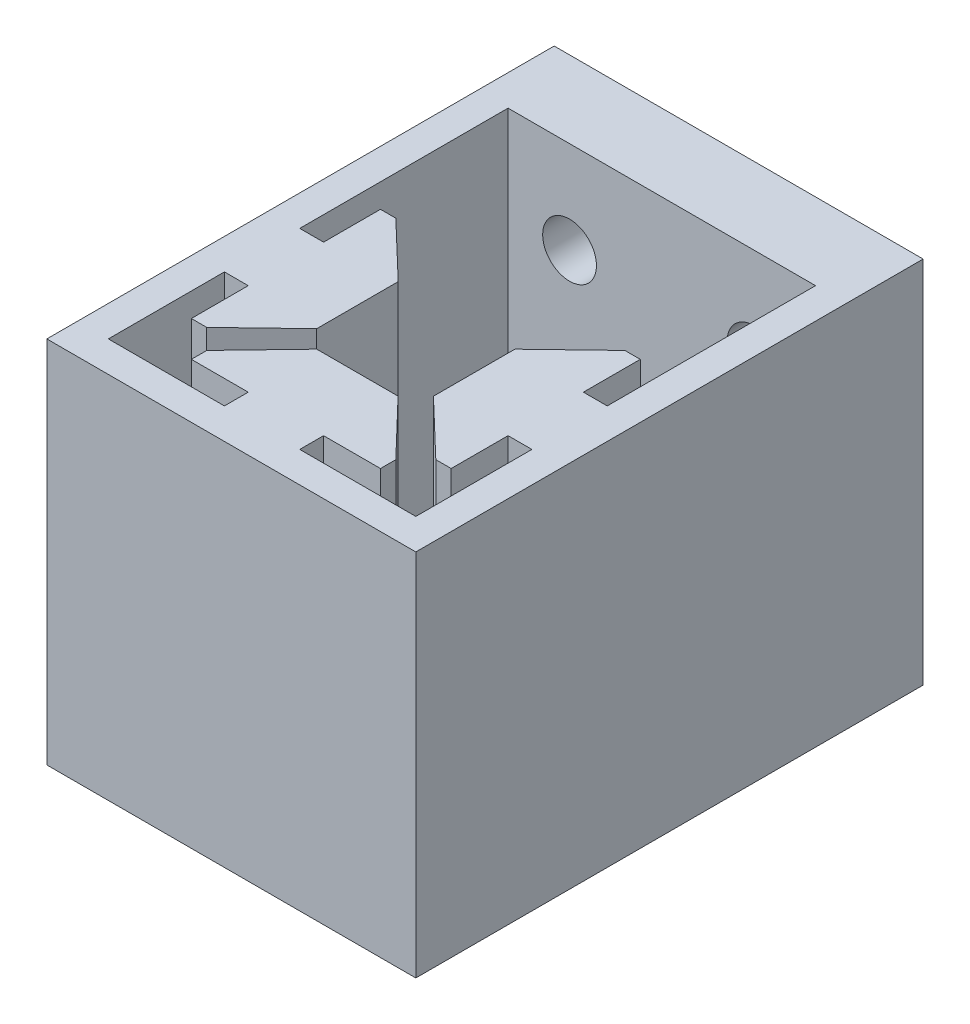
SolidWorks part; units mm, degrees
ref_plane "Plan de face" through (0, 0, 0) normal (0, 0, 1) x (1, 0, 0)
ref_plane "Plan de dessus" through (0, 0, 0) normal (0, 1, 0) x (1, 0, 0)
ref_plane "Plan de droite" through (0, 0, 0) normal (1, 0, 0) x (0, 0, -1)
sketch "Esquisse1" plane through (0, 0, 0) normal (0, 1, 0) x (1, 0, 0)
  line L1 (-12, 14) -> (12, 14)
  line L2 (-12, 14) -> (-12, -14)
  line L3 (-12, -14) -> (12, -14)
  line L4 (12, 14) -> (12, -14)
  line L5 (-12, 14) -> (12, -14) construction
  line L6 (-12, -14) -> (12, 14) construction
  point P0 (0, 0)
extrude "Boss.-Extru.1" add sketch "Esquisse1" along normal blind 24
sketch "Esquisse3" plane through (0, 24, 0) normal (0, 1, 0) x (1, 0, 0)
  line L0 (-10, -12) -> (-2.45, -12)
  line L1 (-2.45, -12) -> (-2.45, -10.45)
  line L2 (-2.45, -10.45) -> (-6.15, -10.45)
  line L3 (-6.15, -10.45) -> (-6.15, -9.45)
  line L4 (-6.15, -9.45) -> (-2.6456, -5.8)
  line L5 (-2.6456, -5.8) -> (2.6456, -5.8)
  line L6 (2.6456, -5.8) -> (6.15, -9.45)
  line L7 (6.15, -9.45) -> (6.15, -10.45)
  line L8 (6.15, -10.45) -> (2.45, -10.45)
  line L9 (2.45, -10.45) -> (2.45, -12)
  line L10 (2.45, -12) -> (10, -12)
  line L11 (10, -12) -> (10, -4.45)
  line L12 (10, -4.45) -> (8.45, -4.45)
  line L13 (8.45, -4.45) -> (8.45, -8.15)
  line L14 (8.45, -8.15) -> (7.45, -8.15)
  line L16 (3.8, -4.6544) -> (3.8, 0.6456)
  line L19 (8.45, 0.45) -> (10, 0.45)
  line L20 (10, 0.45) -> (10, 8)
  line L21 (10, 8) -> (2.45, 8)
  line L22 (2.45, 8) -> (2.45, 6.45)
  line L23 (2.45, 6.45) -> (6.15, 6.45)
  line L24 (6.15, 6.45) -> (6.15, 5.45)
  line L28 (-6.15, 5.45) -> (-6.15, 6.45)
  line L29 (-6.15, 6.45) -> (-2.45, 6.45)
  line L30 (-2.45, 6.45) -> (-2.45, 8)
  line L31 (-2.45, 8) -> (-10, 8)
  line L32 (-10, 8) -> (-10, 0.45)
  line L33 (-10, 0.45) -> (-8.45, 0.45)
  line L34 (-8.45, 0.45) -> (-8.45, 4.15)
  line L35 (-8.45, 4.15) -> (-7.45, 4.15)
  line L36 (-7.45, 4.15) -> (-3.8, 0.6544)
  line L37 (-3.8, 0.6544) -> (-3.8, -4.6456)
  line L38 (-3.8, -4.6456) -> (-7.45, -8.15)
  line L39 (-7.45, -8.15) -> (-8.45, -8.15)
  line L40 (-8.45, -8.15) -> (-8.45, -4.45)
  line L41 (-8.45, -4.45) -> (-10, -4.45)
  line L42 (-10, -4.45) -> (-10, -12)
  line L43 (-12, 14) -> (-12, -14) construction
  line L44 (-12, -14) -> (12, -14) construction
  line L45 (12, -14) -> (12, 14) construction
  line L46 (12, 14) -> (-12, 14) construction
  line L47 (3.8, 0.6456) -> (7.45, 4.15)
  line L48 (7.45, 4.15) -> (8.45, 4.15)
  line L49 (8.45, 0.45) -> (8.45, 4.15)
  line L50 (7.45, -8.15) -> (3.8, -4.6544)
  line L52 (2.6456, 1.8) -> (-2.6456, 1.8)
  line L53 (-2.6456, 1.8) -> (-6.15, 5.45)
  line L54 (6.15, 5.45) -> (2.6456, 1.8)
  dimension "D1" = 2
  dimension "D2" = 2
  dimension "D3" = 2
  dimension "D4" = 2
  dimension "D5" = 6
  dimension "D6" = 6
  dimension "D7" = 7.55
  dimension "D8" = 1.55
  dimension "D9" = 3.7
  dimension "D10" = 1
  dimension "D11" = 2
  dimension "D12" = 5.06
  dimension "D13" = 6.2
  dimension "D14" = 1.55
  dimension "D15" = 3.7
  dimension "D16" = 1
  dimension "D17" = 5.06
  dimension "D18" = 7.55
  dimension "D19" = 7.55
  dimension "D20" = 1.55
  dimension "D21" = 3.7
  dimension "D22" = 2
  dimension "D23" = 6.2
  dimension "D24" = 1
  dimension "D25" = 3.7
  dimension "D26" = 1.55
  dimension "D27" = 5.06
  dimension "D28" = 7.55
  dimension "D29" = 7.55
  dimension "D30" = 7.55
  dimension "D31" = 1.55
  dimension "1.55" = 1.55
  dimension "D32" = 6.2
  dimension "D33" = 3.7
  dimension "D34" = 1
  dimension "D35" = 5.06
  dimension "D36" = 5.3
  dimension "D37" = 3.7
  dimension "D38" = 1
  dimension "D39" = 7.55
  dimension "D40" = 7.55
  dimension "D41" = 6.2
  dimension "D42" = 1.55
  dimension "D43" = 3.7
  dimension "D44" = 1.55
  dimension "D45" = 3.7
  dimension "D46" = 1
  dimension "D47" = 5.2911
  dimension "D48" = 1
  dimension "D49" = 5.06
extrude "Enlèv. mat.-Extru.1" cut sketch "Esquisse3" against normal blind 24
sketch "Esquisse5" plane through (0, 0, -14) normal (0, 0, -1) x (-1, 0, 0)
  line L0 (-12, 0) -> (-12, 24)
  line L1 (-12, 24) -> (12, 24)
  line L2 (12, 24) -> (12, 0)
  line L3 (12, 0) -> (-12, 0)
extrude "Boss.-Extru.2" add sketch "Esquisse5" along normal blind 5
sketch "Esquisse6" plane through (0, 24, 0) normal (0, 1, 0) x (1, 0, 0)
  line L0 (-10, 8) -> (-10, 14)
  line L1 (10, 8) -> (10, 14)
  line L2 (10, 14) -> (-10, 14)
  line L3 (-12, 19) -> (12, 19) construction
  line L48 (-10, -4.45) -> (-10, -12)
  line L49 (-8.45, -4.45) -> (-10, -4.45)
  line L50 (-8.45, -8.15) -> (-8.45, -4.45)
  line L51 (-7.45, -8.15) -> (-8.45, -8.15)
  line L52 (-3.8, -4.6456) -> (-7.45, -8.15)
  line L53 (-3.8, 0.6544) -> (-3.8, -4.6456)
  line L54 (-7.45, 4.15) -> (-3.8, 0.6544)
  line L55 (-8.45, 4.15) -> (-7.45, 4.15)
  line L56 (-8.45, 0.45) -> (-8.45, 4.15)
  line L57 (-10, 0.45) -> (-8.45, 0.45)
  line L58 (-10, 8) -> (-10, 0.45)
  line L59 (-2.45, 8) -> (-10, 8)
  line L60 (-2.45, 6.45) -> (-2.45, 8)
  line L61 (-6.15, 6.45) -> (-2.45, 6.45)
  line L62 (-6.15, 5.45) -> (-6.15, 6.45)
  line L63 (-2.6456, 1.8) -> (-6.15, 5.45)
  line L64 (2.6456, 1.8) -> (-2.6456, 1.8)
  line L65 (6.15, 5.45) -> (2.6456, 1.8)
  line L66 (6.15, 6.45) -> (6.15, 5.45)
  line L67 (2.45, 6.45) -> (6.15, 6.45)
  line L68 (2.45, 8) -> (2.45, 6.45)
  line L69 (10, 8) -> (2.45, 8)
  line L70 (10, 0.45) -> (10, 8)
  line L71 (8.45, 0.45) -> (10, 0.45)
  line L72 (8.45, 4.15) -> (8.45, 0.45)
  line L73 (7.45, 4.15) -> (8.45, 4.15)
  line L74 (3.8, 0.6456) -> (7.45, 4.15)
  line L75 (3.8, -4.6544) -> (3.8, 0.6456)
  line L76 (7.45, -8.15) -> (3.8, -4.6544)
  line L77 (8.45, -8.15) -> (7.45, -8.15)
  line L78 (8.45, -4.45) -> (8.45, -8.15)
  line L79 (10, -4.45) -> (8.45, -4.45)
  line L80 (10, -12) -> (10, -4.45)
  line L81 (2.45, -12) -> (10, -12)
  line L82 (2.45, -10.45) -> (2.45, -12)
  line L83 (6.15, -10.45) -> (2.45, -10.45)
  line L84 (6.15, -9.45) -> (6.15, -10.45)
  line L85 (2.6456, -5.8) -> (6.15, -9.45)
  line L86 (-2.6456, -5.8) -> (2.6456, -5.8)
  line L87 (-6.15, -9.45) -> (-2.6456, -5.8)
  line L88 (-6.15, -10.45) -> (-6.15, -9.45)
  line L89 (-2.45, -10.45) -> (-6.15, -10.45)
  line L90 (-2.45, -12) -> (-2.45, -10.45)
  line L91 (-10, -12) -> (-2.45, -12)
  line L103 (-2.45, 8) -> (-10, 8)
  line L104 (-2.45, 6.45) -> (-2.45, 8)
  line L105 (-6.15, 6.45) -> (-2.45, 6.45)
  line L106 (-6.15, 5.45) -> (-6.15, 6.45)
  line L107 (-2.6456, 1.8) -> (-6.15, 5.45)
  line L108 (2.6456, 1.8) -> (-2.6456, 1.8)
  line L109 (6.15, 5.45) -> (2.6456, 1.8)
  line L110 (6.15, 6.45) -> (6.15, 5.45)
  line L111 (2.45, 6.45) -> (6.15, 6.45)
  line L112 (2.45, 8) -> (2.45, 6.45)
  line L113 (10, 8) -> (2.45, 8)
  dimension "D1" = 5
  dimension "D2" = 0
extrude "Enlèv. mat.-Extru.6" cut sketch "Esquisse6" against normal blind 24
sketch "Esquisse7" plane through (0, 0, -19) normal (0, 0, -1) x (-1, 0, 0)
  line L0 (12, 24) -> (-12, 24) construction
  line L1 (-12, 24) -> (-12, 0) construction
  line L2 (12, 0) -> (12, 24) construction
  line L3 (-12, 0) -> (12, 0) construction
  circle A0 centre (-6, 18) radius 1.75
  circle A1 centre (-6, 6) radius 1.75
  circle A2 centre (6, 6) radius 1.75
  circle A3 centre (6, 18) radius 1.75
  dimension "D1" = 3.5
  dimension "D2" = 3.5
  dimension "D3" = 3.5
  dimension "D4" = 3.5
  dimension "D5" = 6
  dimension "D7" = 6
  dimension "D8" = 6
  dimension "D9" = 6
  dimension "D10" = 6
  dimension "D11" = 6
  dimension "D12" = 6
  dimension "D6" = 6
extrude "Enlèv. mat.-Extru.8" cut sketch "Esquisse7" against normal blind 5
